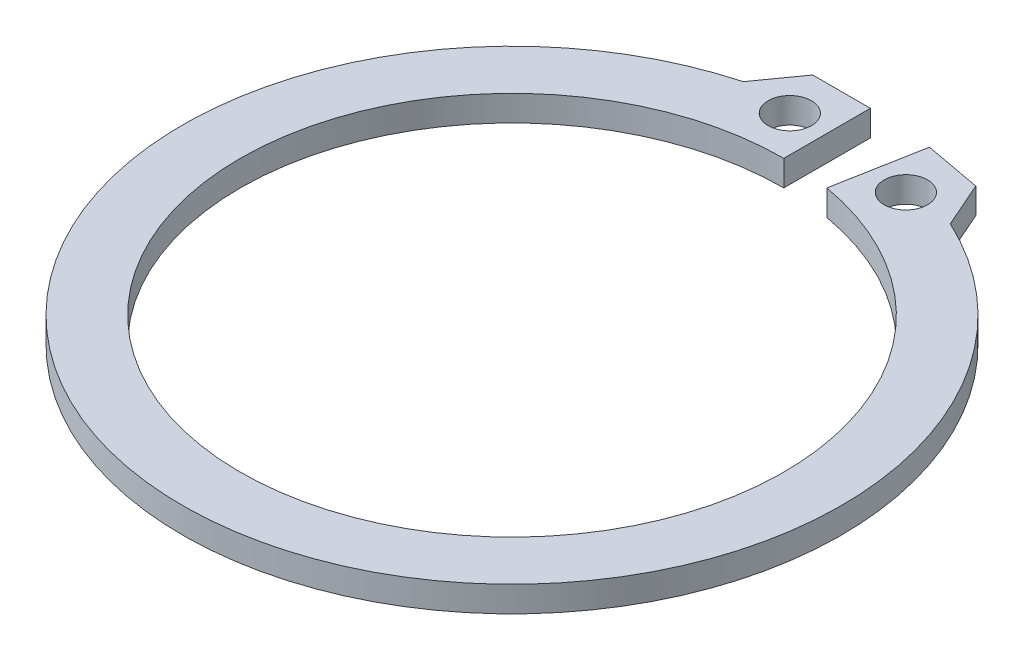
SolidWorks part; units mm, degrees
ref_plane "Front Plane" through (0, 0, 0) normal (0, 0, 1) x (1, 0, 0)
ref_plane "Top Plane" through (0, 0, 0) normal (0, 1, 0) x (1, 0, 0)
ref_plane "Right Plane" through (0, 0, 0) normal (1, 0, 0) x (0, 0, -1)
sketch "Sketch1" plane through (0, 0, 0) normal (0, 1, 0) x (1, 0, 0)
  line L0 (0, 12.4145) -> (-2, 12.4145)
  line L1 (1.6348, 9.2715) -> (2.189, 12.2715)
  line L2 (-2, 12.4145) -> (-3, 11.0132)
  line L3 (0, 12.4145) -> (0, 9.4145)
  line L4 (2.189, 12.2715) -> (4.1557, 11.9081)
  line L5 (4.1557, 11.9081) -> (4.8489, 10.3334)
  arc A0 (1.6348, 9.2715) -> (0, 9.4145) centre (0, 0) cw
  arc A1 (4.8489, 10.3334) -> (-3, 11.0132) centre (0, 0) cw
  arc A2 (1.9821, 11.2411) -> (0, 11.4145) centre (0, 0) cw construction
  dimension "D1" = 2
  dimension "D2" = 3
  dimension "D3" = 1.4013
extrude "Boss-Extrude1" add sketch "Sketch1" along normal blind 0.889
sketch "Sketch4" plane through (0, 0.889, 0) normal (0, 1, 0) x (1, 0, 0)
  line L0 (-1.25, 12.4145) -> (-1.25, 9.3311) construction
  line L1 (0, 12.4145) -> (-2, 12.4145) construction
  line L2 (3.4182, 12.0444) -> (2.8507, 8.9725) construction
  line L3 (4.1557, 11.9081) -> (2.189, 12.2715) construction
  arc A0 (0, 9.4145) -> (1.6348, 9.2715) centre (0, 0) ccw construction
  circle A1 centre (-1.25, 10.8728) radius 0.75
  circle A2 centre (3.1345, 10.5084) radius 0.75
  dimension "D1" = 1.25
  dimension "D2" = 1.25
extrude "Cut-Extrude2" cut sketch "Sketch4" against normal blind 0.889
